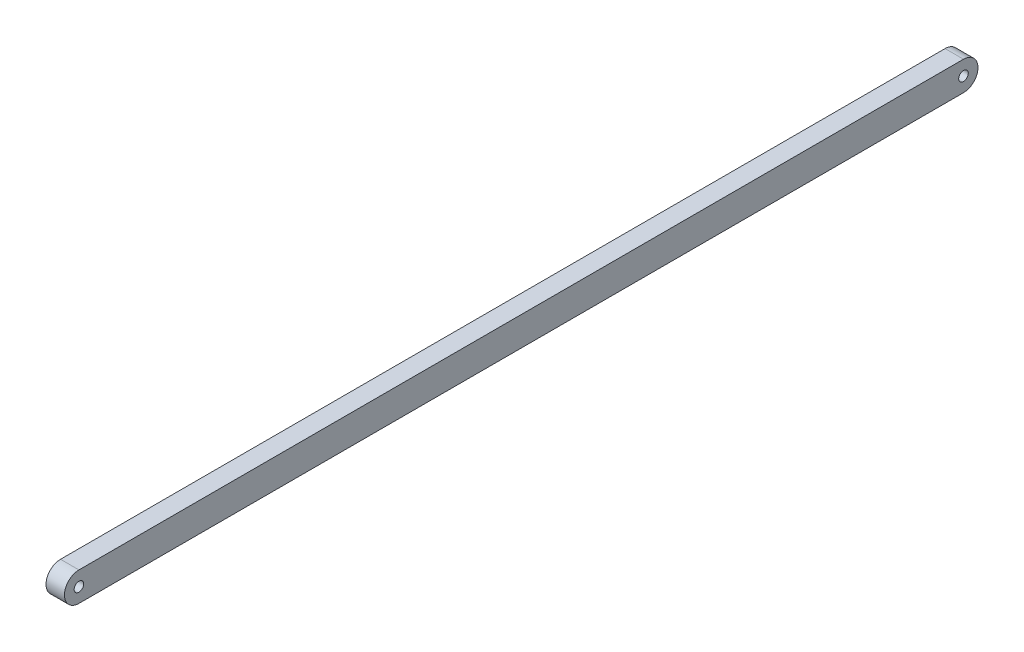
SolidWorks part; units mm, degrees
ref_plane "Front Plane" through (0, 0, 0) normal (0, 0, 1) x (1, 0, 0)
ref_plane "Top Plane" through (0, 0, 0) normal (0, 1, 0) x (1, 0, 0)
ref_plane "Right Plane" through (0, 0, 0) normal (1, 0, 0) x (0, 0, -1)
sketch "Sketch1" plane through (0, 0, 0) normal (1, 0, 0) x (0, 0, -1)
  line L0 (-152.4, 5) -> (152.4, 5)
  line L1 (-152.4, -5) -> (152.4, -5)
  line L2 (0, 5) -> (0, -5) construction
  circle A0 centre (-152.4, 0) radius 1.65
  arc A1 (-152.4, 5) -> (-152.4, -5) centre (-152.4, 0) ccw
  arc A2 (152.4, 5) -> (152.4, -5) centre (152.4, 0) cw
  circle A3 centre (152.4, 0) radius 1.65
  dimension "D1" = 304.8
  dimension "D2" = 3.3
  dimension "D3" = 10
extrude "Boss-Extrude1" add sketch "Sketch1" along normal blind 6.35
